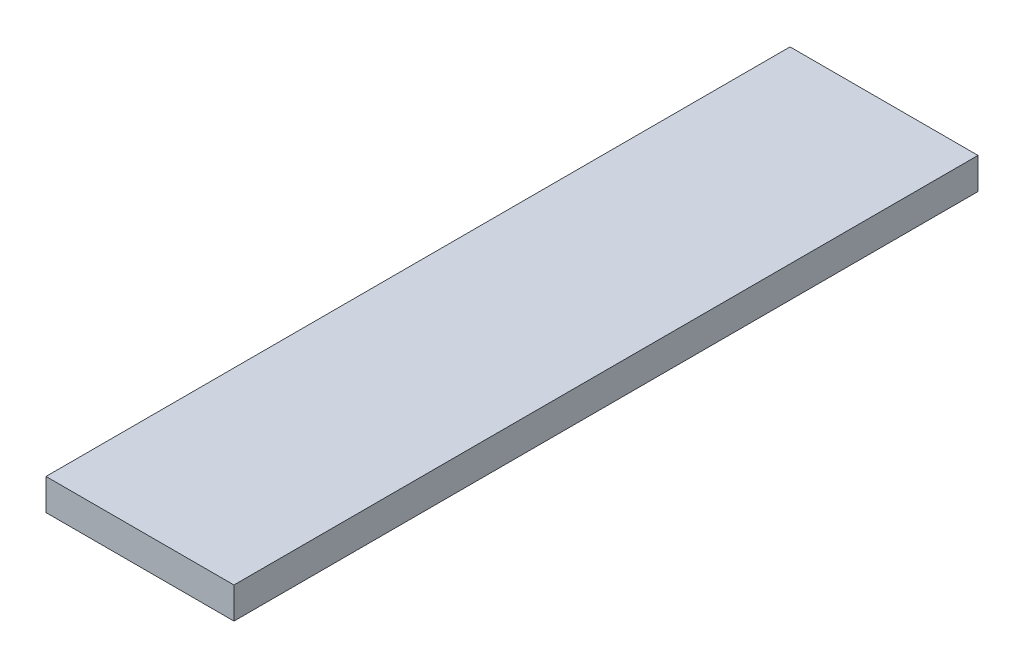
SolidWorks part; units mm, degrees
material "Beech"
ref_plane "Front Plane" through (0, 0, 0) normal (0, 0, 1) x (1, 0, 0)
ref_plane "Top Plane" through (0, 0, 0) normal (0, 1, 0) x (1, 0, 0)
ref_plane "Right Plane" through (0, 0, 0) normal (1, 0, 0) x (0, 0, -1)
sketch "Sketch1" plane through (0, 0, 0) normal (0, 1, 0) x (1, 0, 0)
  line L1 (-22.9548, 29.841) -> (1.0452, 29.841)
  line L2 (-22.9548, 29.841) -> (-22.9548, -65.159)
  line L3 (-22.9548, -65.159) -> (1.0452, -65.159)
  line L4 (1.0452, 29.841) -> (1.0452, -65.159)
  dimension "D1" = 95
  dimension "D2" = 24
extrude "Boss-Extrude1" add sketch "Sketch1" along normal blind 4
